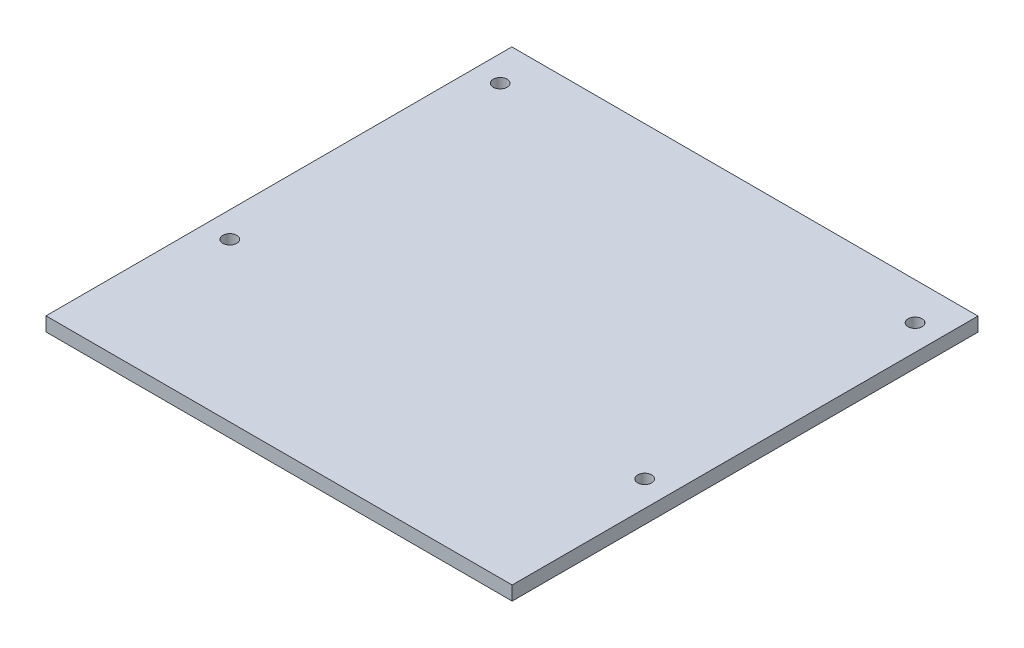
SolidWorks part; units mm, degrees
ref_plane "Front Plane" through (0, 0, 0) normal (0, 0, 1) x (1, 0, 0)
ref_plane "Top Plane" through (0, 0, 0) normal (0, 1, 0) x (1, 0, 0)
ref_plane "Right Plane" through (0, 0, 0) normal (1, 0, 0) x (0, 0, -1)
sketch "Sketch1" plane through (0, 0, 0) normal (0, 1, 0) x (1, 0, 0)
  line L0 (-50, 0) -> (50, 0)
  line L1 (-50, -4.4636) -> (50, -4.4636)
  line L2 (-50, -4.4636) -> (-50, 4.4636)
  line L3 (-50, 4.4636) -> (50, 4.4636)
  line L4 (50, -4.4636) -> (50, 4.4636)
  line L5 (-50, -4.4636) -> (50, 4.4636) construction
  line L6 (-50, 4.4636) -> (50, -4.4636) construction
  line L8 (-48.25, -0.9) -> (48.25, -0.9)
  line L9 (-48.25, -0.9) -> (-48.25, 0.9)
  line L10 (-48.25, 0.9) -> (48.25, 0.9)
  line L11 (48.25, -0.9) -> (48.25, 0.9)
  line L12 (-48.25, -0.9) -> (48.25, 0.9) construction
  line L13 (-48.25, 0.9) -> (48.25, -0.9) construction
  point P0 (0, 0)
  point P6 (0, 0)
  point P9 (0, 0)
  dimension "D1" = 100
  dimension "D2" = 1.75
  dimension "D3" = 1.75
  dimension "D4" = 1.8
extrude "Boss-Extrude1" add sketch "Sketch1" along normal blind 3 contours L11 L8 L9 L0 L2 L1 L4 | L11 L0 L4 L3 L2 L9 L10 | L8 L11 L0 L9 | L0 L11 L10 L9
sketch "Sketch2" plane through (0, 0, -4.4636) normal (0, 0, -1) x (-1, 0, 0)
  line L1 (-50, 0) -> (50, 0)
  line L2 (-50, 0) -> (-50, 3)
  line L3 (-50, 3) -> (50, 3)
  line L4 (50, 0) -> (50, 3)
extrude "Boss-Extrude2" add sketch "Sketch2" along normal blind 91
sketch "Sketch4" plane through (0, 3, 0) normal (0, 1, 0) x (1, 0, 0)
  line L0 (-50, 95.4636) -> (50, 95.4636) construction
  line L1 (-44.5, 87.4636) -> (44.5, 87.4636)
  line L2 (-44.5, 87.4636) -> (-44.5, 29.4636)
  line L3 (-44.5, 29.4636) -> (44.5, 29.4636)
  line L4 (44.5, 87.4636) -> (44.5, 29.4636)
  line L5 (-50, -4.4636) -> (-50, 95.4636) construction
  line L7 (50, -4.4636) -> (50, 95.4636) construction
  circle A0 centre (-44.5, 87.4636) radius 1.5
  circle A1 centre (44.5, 87.4636) radius 1.5
  circle A2 centre (-44.5, 29.4636) radius 1.5
  circle A3 centre (44.5, 29.4636) radius 1.5
  dimension "D6" = 3
  dimension "D7" = 3
  dimension "D8" = 3
  dimension "D9" = 3
  dimension "D1" = 89
  dimension "D2" = 58
  dimension "D3" = 8
  dimension "D4" = 5.5
  dimension "D5" = 5.5
extrude "Cut-Extrude1" cut sketch "Sketch4" against normal through all contours A0 | A1 | A2 | A3
fillet "Fillet1" [suppressed] radius 10
